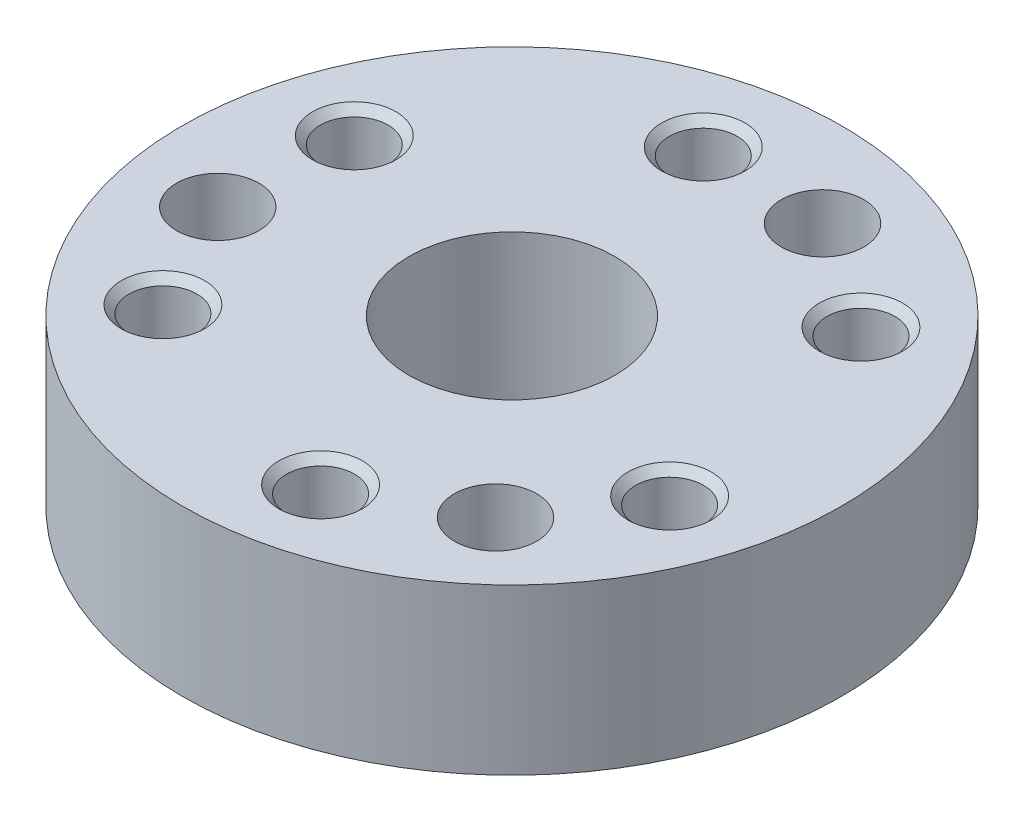
SolidWorks part; units mm, degrees
ref_plane "前视基准面" through (0, 0, 0) normal (0, 0, 1) x (1, 0, 0)
ref_plane "上视基准面" through (0, 0, 0) normal (0, 1, 0) x (1, 0, 0)
ref_plane "右视基准面" through (0, 0, 0) normal (1, 0, 0) x (0, 0, -1)
other "Configuration Table"
sketch "草图1" plane through (0, 0, 0) normal (0, 1, 0) x (1, 0, 0)
  circle A0 centre (0, 0) radius 16
  dimension "D1" = 32
extrude "凸台-拉伸1" add sketch "草图1" along normal blind 8
sketch "草图2" plane through (0, 8, 0) normal (0, 1, 0) x (1, 0, 0)
  line L0 (0, 0) -> (-22.4438, 0) construction
  line L1 (-22.4438, 0) -> (23.514, 0) construction
  line L2 (0, 16.5271) -> (0, -18.4229) construction
  circle A0 centre (0, 0) radius 12 construction
  circle A1 centre (-2.4566, 11.7458) radius 2
  circle A2 centre (8.9439, 8.0004) radius 2
  circle A3 centre (11.4005, -3.7454) radius 2
  circle A4 centre (2.4566, -11.7458) radius 2
  circle A5 centre (-8.9439, -8.0004) radius 2
  circle A6 centre (-11.4005, 3.7454) radius 2
  point P22 (0, 0)
  dimension "D1" = 24
  dimension "D2" = 4
  dimension "D3" = 6
hole_wizard "M4 螺纹孔1" positions "草图3" profile "草图4" tap size "M4" standard "GB"
sketch "草图3" plane through (0, 8, 0) normal (0, 1, 0) x (1, 0, 0)
  point P0 (-11.4005, 3.7454)
  point P3 (-2.4566, 11.7458)
  point P6 (8.9439, 8.0004)
  point P9 (11.4005, -3.7454)
  point P12 (2.4566, -11.7458)
  point P15 (-8.9439, -8.0004)
sketch "草图4" plane through (-11.4005, 8, -3.7454) normal (1, 0, 0) x (0, 0, 1)
  line L0 (0, 0) -> (0, 6.9914)
  line L1 (0, 6.9914) -> (1.65, 6)
  line L2 (1.65, 6) -> (1.65, 0.375)
  line L3 (1.65, 0.375) -> (2.025, 0)
  line L5 (2.025, 0) -> (0, 0)
  line L6 (-1.65, 0.375) -> (-2.025, 0) construction
  line L10 (0, 6.9914) -> (-1.65, 6) construction
  line L11 (0, -6.35) -> (0, 107.95) construction
  dimension "螺纹孔钻头直径" = 3.3
  dimension "螺纹孔钻头深度" = 6
  dimension "近端锥形沉头孔直径" = 4.05
  dimension "近端锥形沉头孔角度" = 90
  dimension "导头角度" = 118
cosmetic thread "孔螺蚊线1" parameters "D1"=6, "D2"=4
cosmetic thread "孔螺蚊线2" parameters "D1"=6, "D2"=4
cosmetic thread "孔螺蚊线3" parameters "D1"=6, "D2"=4
cosmetic thread "孔螺蚊线4" parameters "D1"=6, "D2"=4
cosmetic thread "孔螺蚊线5" parameters "D1"=6, "D2"=4
cosmetic thread "孔螺蚊线6" parameters "D1"=6, "D2"=4
sketch "草图5" plane through (0, 8, 0) normal (0, 1, 0) x (1, 0, 0)
  circle A0 centre (3.6469, 11.4324) radius 2
  circle A1 centre (0, 0) radius 12 construction
  circle A2 centre (8.0773, -8.8745) radius 2
  circle A3 centre (-11.7242, -2.5579) radius 2
  point P10 (0, 0)
  dimension "D1" = 4
  dimension "D2" = 3
extrude "切除-拉伸1" cut sketch "草图5" against normal blind 8 contours A0 | A2 | A3
sketch "草图6" plane through (0, 8, 0) normal (0, 1, 0) x (1, 0, 0)
  circle A0 centre (0, 0) radius 5
  dimension "D1" = 10
extrude "切除-拉伸2" cut sketch "草图6" against normal blind 8 contours A0
